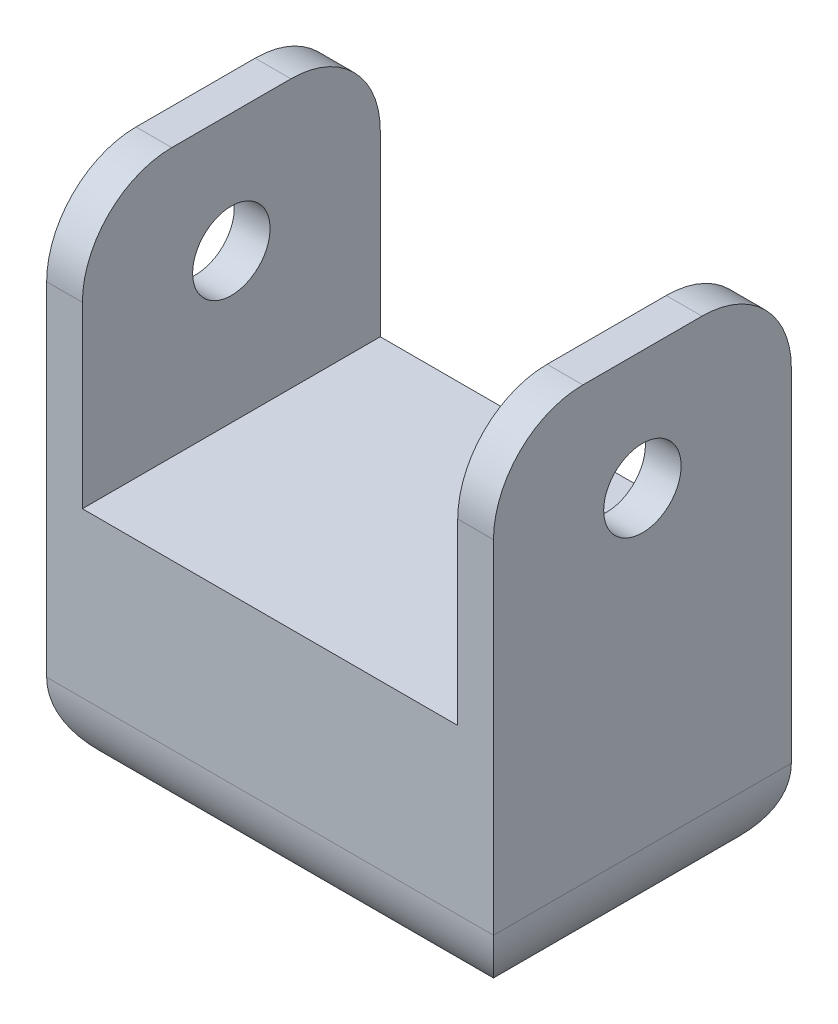
SolidWorks part; units mm, degrees
ref_plane "Front Plane" through (0, 0, 0) normal (0, 0, 1) x (1, 0, 0)
ref_plane "Top Plane" through (0, 0, 0) normal (0, 1, 0) x (1, 0, 0)
ref_plane "Right Plane" through (0, 0, 0) normal (1, 0, 0) x (0, 0, -1)
sketch "Sketch1" plane through (0, 0, 0) normal (0, 1, 0) x (1, 0, 0)
  line L1 (-19.05, 12.7) -> (19.05, 12.7)
  line L2 (-19.05, 12.7) -> (-19.05, -12.7)
  line L3 (-19.05, -12.7) -> (19.05, -12.7)
  line L4 (19.05, 12.7) -> (19.05, -12.7)
  line L5 (-19.05, 12.7) -> (19.05, -12.7) construction
  line L6 (-19.05, -12.7) -> (19.05, 12.7) construction
  point P0 (0, 0)
  dimension "D1" = 38.1
  dimension "D2" = 25.4
extrude "Boss-Extrude1" add sketch "Sketch1" along normal blind 25.4
sketch "Sketch2" plane through (0, 25.4, 0) normal (0, 1, 0) x (1, 0, 0)
  line L0 (19.05, 12.7) -> (-19.05, 12.7) construction
  line L1 (-16.002, 12.7) -> (16.002, 12.7)
  line L2 (-16.002, 12.7) -> (-16.002, -12.7)
  line L3 (-16.002, -12.7) -> (16.002, -12.7)
  line L4 (16.002, 12.7) -> (16.002, -12.7)
  line L5 (-19.05, -12.7) -> (19.05, -12.7) construction
  dimension "D1" = 32.004
  dimension "D2" = 16.002
extrude "Cut-Extrude1" cut sketch "Sketch2" against normal blind 22.86
sketch "Sketch3" plane through (-19.05, 0, 0) normal (-1, 0, 0) x (0, 0, 1)
  line L0 (-12.7, 0) -> (12.7, 0) construction
  circle A0 centre (0, 15.24) radius 3.302
  point P4 (0, 15.24)
  dimension "D1" = 6.604
  dimension "D2" = 15.24
extrude "Cut-Extrude2" cut sketch "Sketch3" against normal through all
fillet "Fillet1" radius 7.62 4 edges at (17.526, 25.4, 12.7) (17.526, 25.4, -12.7) (-17.526, 25.4, 12.7) (-17.526, 25.4, -12.7)
sketch "Sketch4" plane through (0, 0, 0) normal (0, -1, 0) x (1, 0, 0)
  line L1 (-19.05, 12.7) -> (19.05, 12.7)
  line L2 (-19.05, 12.7) -> (-19.05, -12.7)
  line L3 (-19.05, -12.7) -> (19.05, -12.7)
  line L4 (19.05, 12.7) -> (19.05, -12.7)
extrude "Boss-Extrude2" add sketch "Sketch4" along normal blind 19.05
fillet "Fillet2" radius 7.62 4 edges at (0, -19.05, 12.7) (19.05, -19.05, 0) (0, -19.05, -12.7) (-19.05, -19.05, 0)
